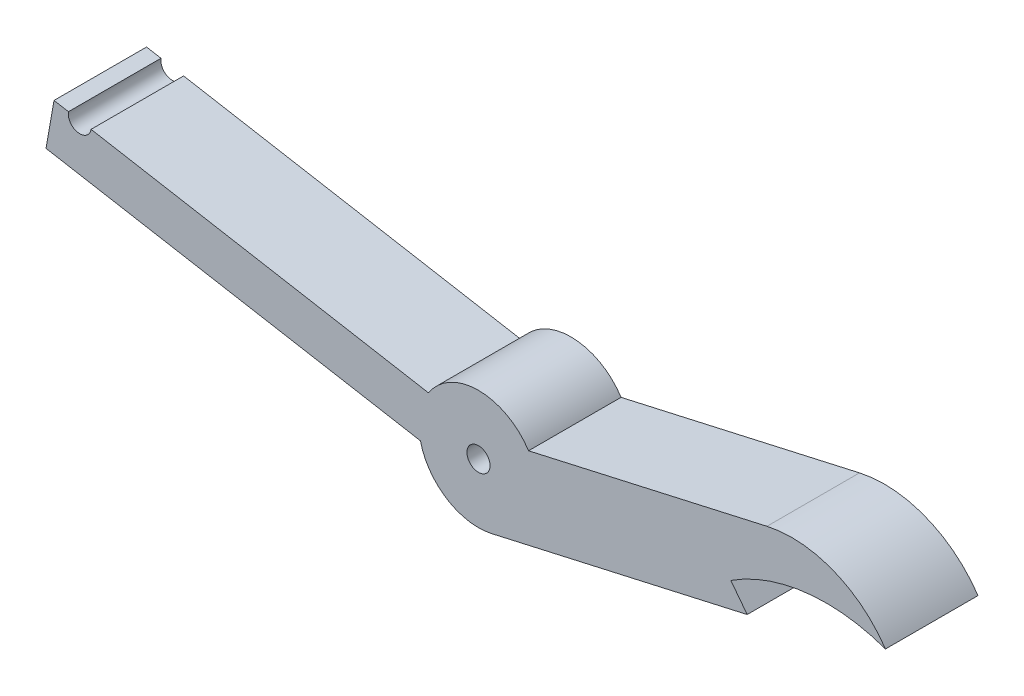
SolidWorks part; units mm, degrees
material "Oak"
ref_plane "Front Plane" through (0, 0, 0) normal (0, 0, 1) x (1, 0, 0)
ref_plane "Top Plane" through (0, 0, 0) normal (0, 1, 0) x (1, 0, 0)
ref_plane "Right Plane" through (0, 0, 0) normal (1, 0, 0) x (0, 0, -1)
sketch "Sketch1" plane through (0, 0, 0) normal (0, 0, 1) x (1, 0, 0)
  line L0 (0, 0) -> (50.8, 0) construction
  line L1 (0, 0) -> (47.7364, -17.3746) construction
  line L2 (34.6352, 2.889) -> (36.8811, -0.0471) construction
  line L3 (61.6179, -32.3874) -> (63.8638, -35.3235) construction
  line L4 (-6.858, 4.4332) -> (-53.1755, 12.6003)
  line L5 (1.7669, -7.9727) -> (36.8811, -0.0471)
  line L6 (36.8811, -0.0471) -> (34.6352, 2.889)
  line L7 (6.8698, 4.4149) -> (39.5958, 11.8014)
  line L8 (0, 0) -> (-42.9058, 0) construction
  line L9 (-7.9606, -1.8203) -> (-59.36, 7.2428)
  line L10 (-58.2573, 13.4963) -> (-59.36, 7.2428)
  line L11 (-56.2773, 13.1472) -> (-58.2573, 13.4963)
  line L12 (-58.8087, 10.3696) -> (0, 0) construction
  circle A0 centre (0, 0) radius 50.8 construction
  circle A1 centre (47.7364, -17.3746) radius 16.6688 construction
  arc A2 (63.8638, -35.3235) -> (34.6352, 2.889) centre (47.7364, -17.3746) ccw construction
  arc A3 (61.6179, -32.3874) -> (36.8811, -0.0471) centre (47.7364, -17.3746) ccw construction
  circle A4 centre (0, 0) radius 1.5875
  arc A5 (6.8698, 4.4149) -> (-6.858, 4.4332) centre (0, 0) ccw
  arc A6 (39.5958, 11.8014) -> (55.8608, 5.3465) centre (43.0086, -3.319) cw
  arc A7 (-56.2773, 13.1472) -> (-53.1755, 12.6003) centre (-54.7264, 12.8737) ccw
  arc A8 (-7.9606, -1.8203) -> (1.7669, -7.9727) centre (0, 0) ccw
  arc A9 (34.6352, 2.889) -> (55.8608, 5.3465) centre (47.7364, -17.3746) cw
  point P6 (66.9025, -2.7146)
  dimension "D3" = 33.3375
  dimension "D4" = 48.26
  dimension "D5" = 40.894
  dimension "D9" = 1.5748
  dimension "D11" = 3.175
  dimension "D12" = 8.1661
  dimension "D13" = 24.13
  dimension "D14" = 15.5007
  dimension "D1" = 50.8
  dimension "D2" = 20
  dimension "D6" = 22.225
  dimension "D7" = 10
  dimension "D8" = 6.35
  dimension "D10" = 3.5854
  dimension "D15" = 12.719
extrude "Boss-Extrude1" add sketch "Sketch1" along normal mid plane 12.7
